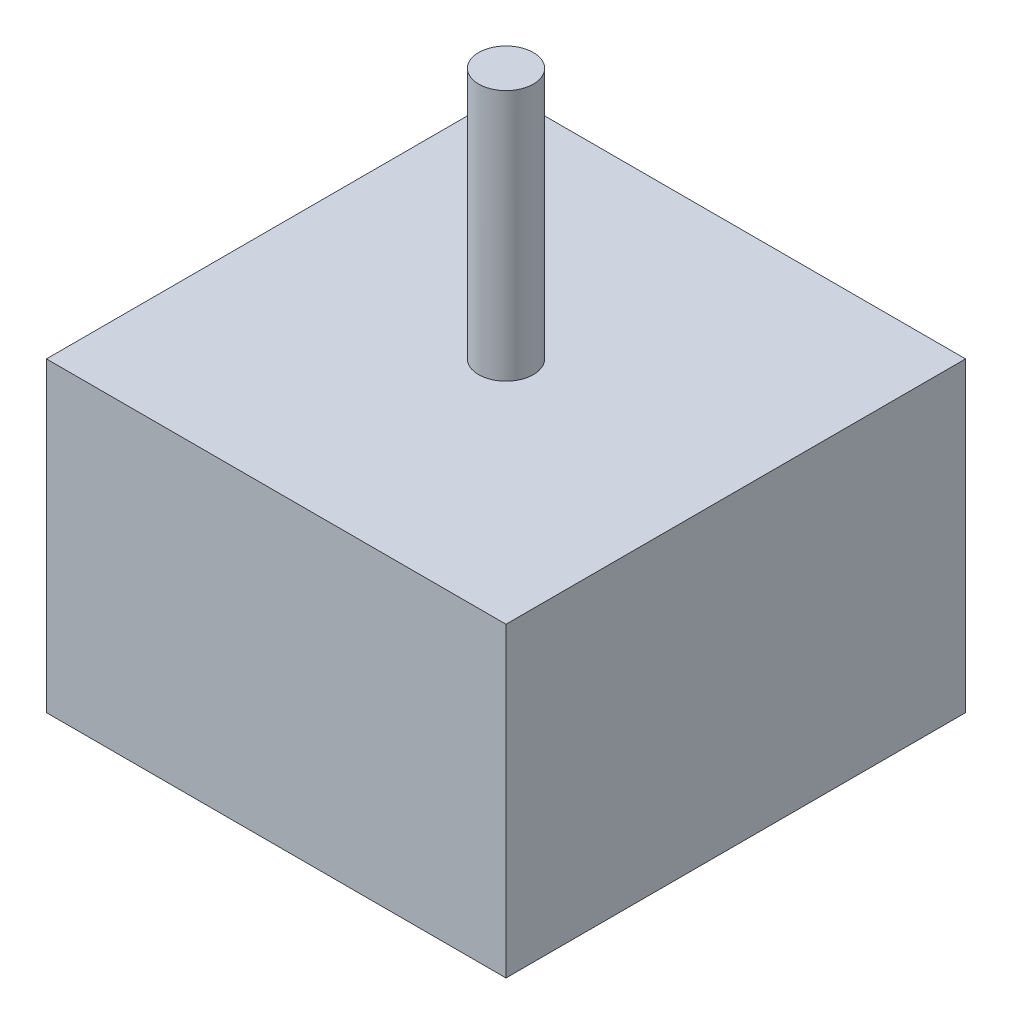
SolidWorks part; units mm, degrees
ref_plane "前视基准面" through (0, 0, 0) normal (0, 0, 1) x (1, 0, 0)
ref_plane "上视基准面" through (0, 0, 0) normal (0, 1, 0) x (1, 0, 0)
ref_plane "右视基准面" through (0, 0, 0) normal (1, 0, 0) x (0, 0, -1)
other "Configuration Table"
sketch "草图1" plane through (0, 0, 0) normal (1, 0, 0) x (0, 0, -1)
  line L1 (0, 0) -> (42, 0)
  line L2 (0, 0) -> (0, 28)
  line L3 (0, 28) -> (42, 28)
  line L4 (42, 0) -> (42, 28)
  dimension "D1" = 42
  dimension "D2" = 28
extrude "凸台-拉伸1" add sketch "草图1" along normal blind 42
sketch "草图2" plane through (0, 28, 0) normal (0, 1, 0) x (1, 0, 0)
  line L0 (42, 42) -> (0, 42) construction
  line L1 (42, 0) -> (42, 42) construction
  circle A0 centre (21, 21) radius 2.5
  dimension "D1" = 21
  dimension "D2" = 21
  dimension "D3" = 5
extrude "凸台-拉伸2" add sketch "草图2" along normal blind 23
